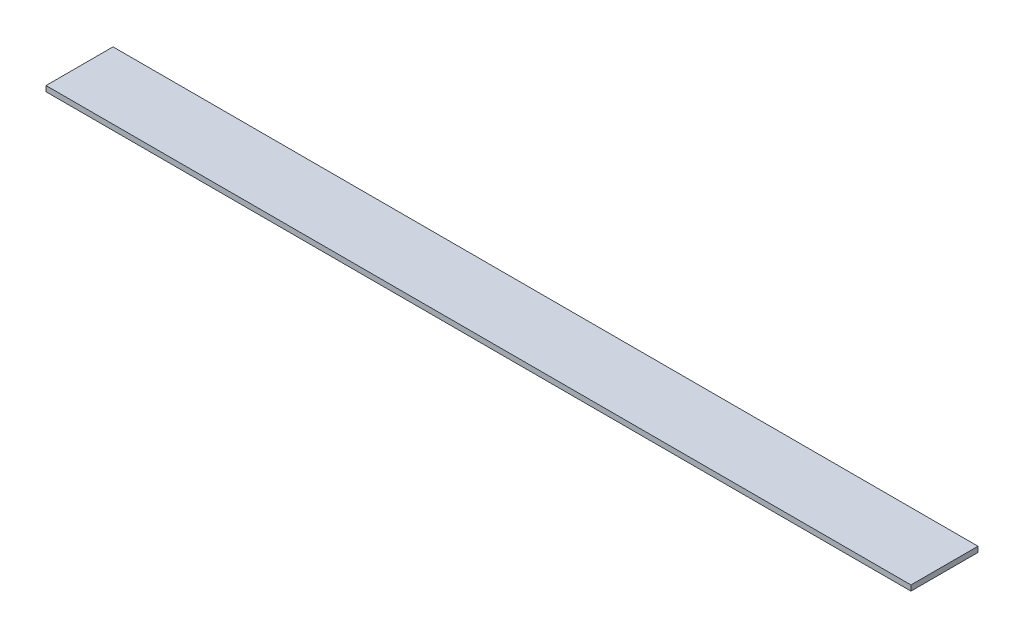
SolidWorks part; units mm, degrees
ref_plane "Front Plane" through (0, 0, 0) normal (0, 0, 1) x (1, 0, 0)
ref_plane "Top Plane" through (0, 0, 0) normal (0, 1, 0) x (1, 0, 0)
ref_plane "Right Plane" through (0, 0, 0) normal (1, 0, 0) x (0, 0, -1)
sketch "Sketch1" plane through (0, 0, 0) normal (0, 1, 0) x (1, 0, 0)
  line L1 (-254, 19.685) -> (254, 19.685)
  line L2 (-254, 19.685) -> (-254, -19.685)
  line L3 (-254, -19.685) -> (254, -19.685)
  line L4 (254, 19.685) -> (254, -19.685)
  line L5 (-254, 19.685) -> (254, -19.685) construction
  line L6 (-254, -19.685) -> (254, 19.685) construction
  point P0 (0, 0)
  dimension "D1" = 39.37
  dimension "D2" = 508
extrude "Boss-Extrude1" add sketch "Sketch1" along normal blind 3.175
